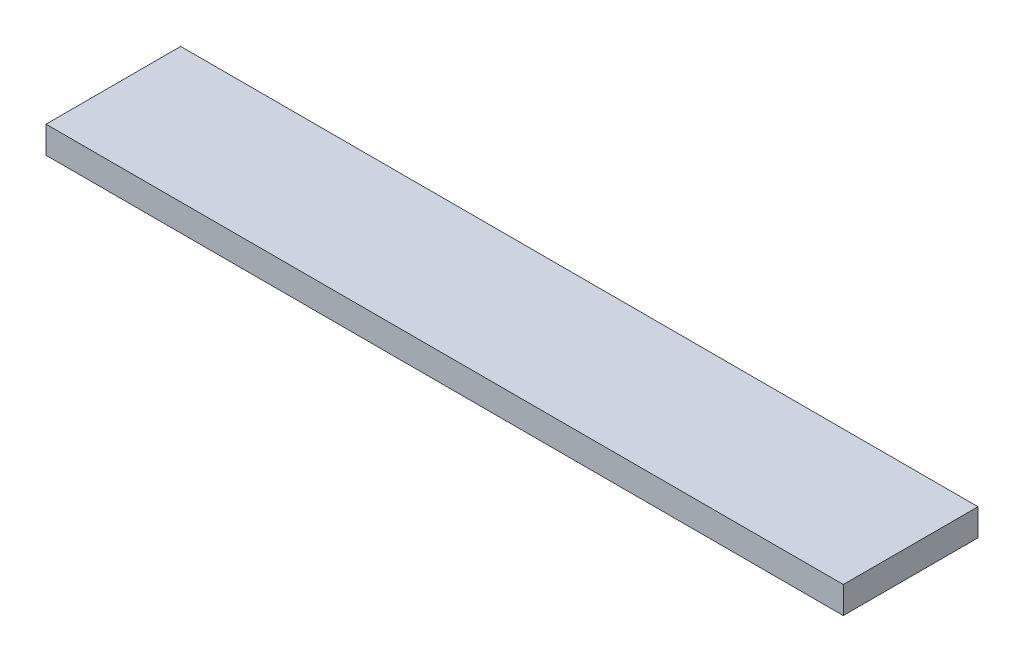
SolidWorks part; units mm, degrees
material "Plain Carbon Steel"
ref_plane "Front Plane" through (0, 0, 0) normal (0, 0, 1) x (1, 0, 0)
ref_plane "Top Plane" through (0, 0, 0) normal (0, 1, 0) x (1, 0, 0)
ref_plane "Right Plane" through (0, 0, 0) normal (1, 0, 0) x (0, 0, -1)
sketch "Sketch1" plane through (0, 0, 0) normal (0, 1, 0) x (1, 0, 0)
  line L1 (-148, 25) -> (148, 25)
  line L2 (-148, 25) -> (-148, -25)
  line L3 (-148, -25) -> (148, -25)
  line L4 (148, 25) -> (148, -25)
  line L5 (-148, 25) -> (148, -25) construction
  line L6 (-148, -25) -> (148, 25) construction
  point P0 (0, 0)
  dimension "D1" = 50
  dimension "D2" = 296
extrude "Boss-Extrude1" add sketch "Sketch1" along normal blind 10
